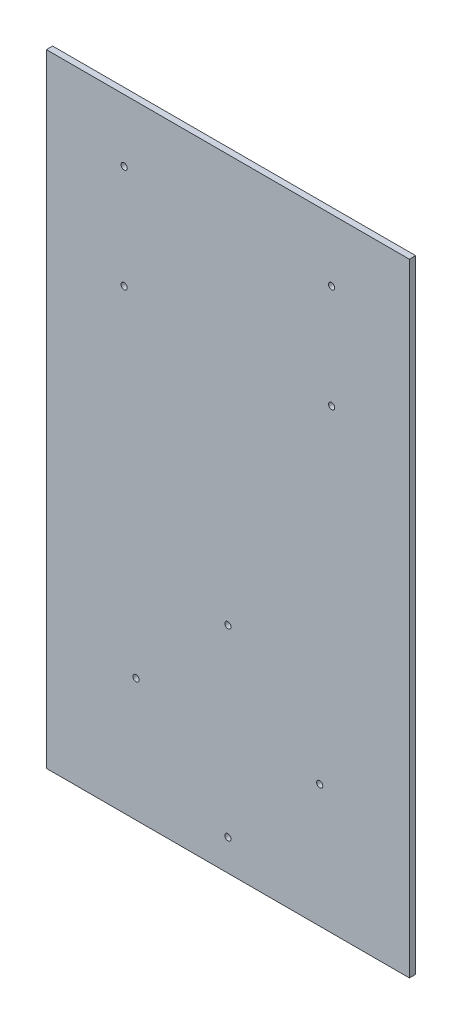
SolidWorks part; units mm, degrees
ref_plane "前视基准面" through (0, 0, 0) normal (0, 0, 1) x (1, 0, 0)
ref_plane "上视基准面" through (0, 0, 0) normal (0, 1, 0) x (1, 0, 0)
ref_plane "右视基准面" through (0, 0, 0) normal (1, 0, 0) x (0, 0, -1)
sketch "草图1" plane through (0, 0, 0) normal (0, 0, 1) x (1, 0, 0)
  line L1 (-87.5, -150) -> (87.5, -150)
  line L2 (-87.5, -150) -> (-87.5, 150)
  line L3 (-87.5, 150) -> (87.5, 150)
  line L4 (87.5, -150) -> (87.5, 150)
  line L5 (-87.5, -150) -> (87.5, 150) construction
  line L6 (-87.5, 150) -> (87.5, -150) construction
  point P0 (0, 0)
extrude "凸台-拉伸1" add sketch "草图1" along normal blind 3
sketch "草图2" plane through (0, 0, 3) normal (0, 0, 1) x (1, 0, 0)
  circle A0 centre (0, -135) radius 1.5
  circle A1 centre (-44.25, -90.75) radius 1.5
  circle A2 centre (0, -46.5) radius 1.5
  circle A3 centre (44.25, -90.75) radius 1.5
  point P18 (0, -90.75)
  dimension "D1" = 4
extrude "切除-拉伸1" cut sketch "草图2" against normal blind 3
sketch "草图3" plane through (0, 0, 3) normal (0, 0, 1) x (1, 0, 0)
  circle A0 centre (50, 70) radius 1.5
  circle A1 centre (50, 120) radius 1.5
  circle A2 centre (-50, 120) radius 1.5
  circle A3 centre (-50, 70) radius 1.5
extrude "切除-拉伸2" cut sketch "草图3" against normal blind 3
